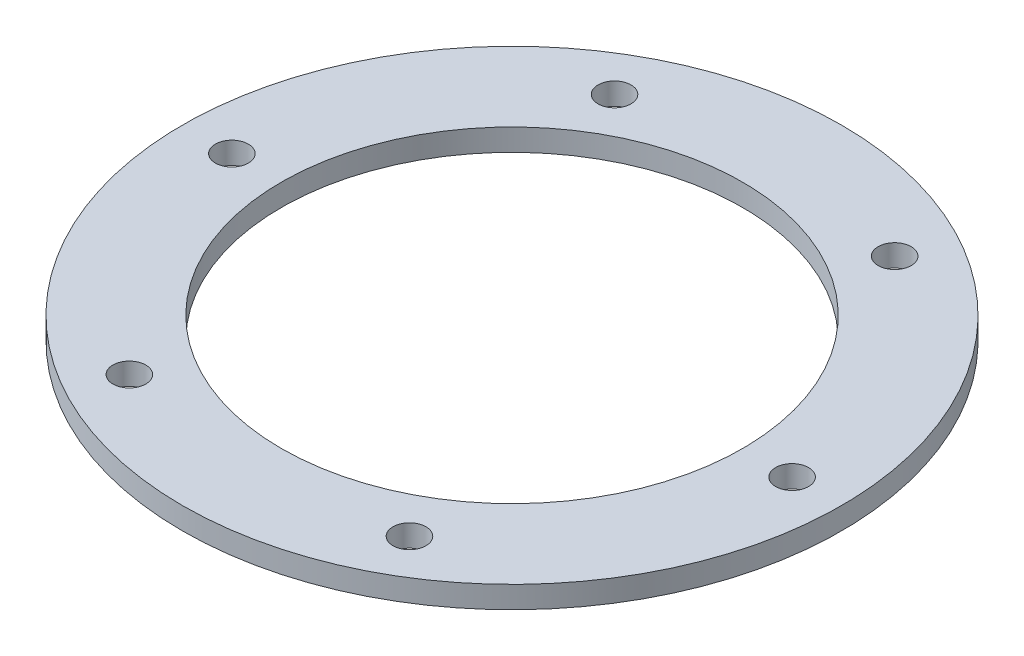
SolidWorks part; units mm, degrees
ref_plane "Front Plane" through (0, 0, 0) normal (0, 0, 1) x (1, 0, 0)
ref_plane "Top Plane" through (0, 0, 0) normal (0, 1, 0) x (1, 0, 0)
ref_plane "Right Plane" through (0, 0, 0) normal (1, 0, 0) x (0, 0, -1)
sketch "Sketch1" plane through (0, 0, 0) normal (0, 1, 0) x (1, 0, 0)
  line L0 (0, 0) -> (43.7646, 0) construction
  line L1 (43.7646, 0) -> (-48.6292, 0) construction
  line L2 (-48.6292, 0) -> (0, 0) construction
  line L3 (0, 0) -> (22.035, -38.1657) construction
  line L4 (22.035, -38.1657) -> (-21.6364, 37.4753) construction
  line L5 (0, 0) -> (19.8864, 34.4443) construction
  line L6 (19.8864, 34.4443) -> (-18.557, -32.1416) construction
  circle A0 centre (0, 0) radius 30
  circle A1 centre (0, 0) radius 21
  circle A2 centre (0, 0) radius 25.5 construction
  circle A3 centre (-12.75, 22.0836) radius 1.5
  circle A4 centre (12.75, 22.0836) radius 1.5
  circle A5 centre (25.5, 0) radius 1.5
  circle A6 centre (12.75, -22.0836) radius 1.5
  circle A7 centre (-12.75, -22.0836) radius 1.5
  circle A8 centre (-25.5, 0) radius 1.5
  dimension "D1" = 60
  dimension "D3" = 42
  dimension "D2" = 60
extrude "Boss-Extrude1" add sketch "Sketch1" along normal blind 2
